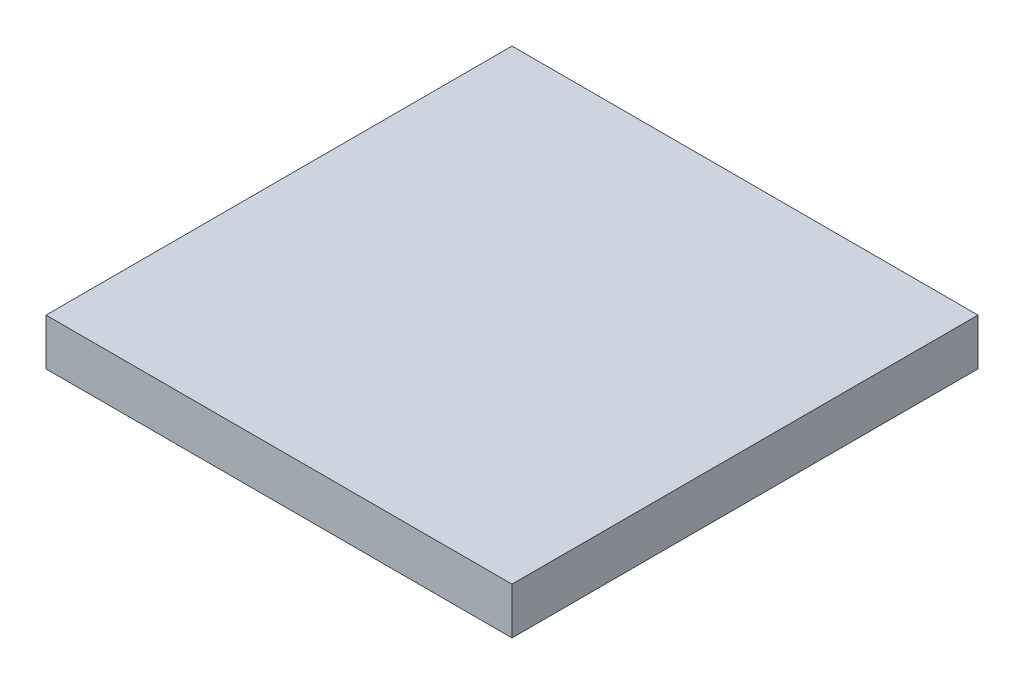
SolidWorks part; units mm, degrees
material "Glass"
ref_plane "Front Plane" through (0, 0, 0) normal (0, 0, 1) x (1, 0, 0)
ref_plane "Top Plane" through (0, 0, 0) normal (0, 1, 0) x (1, 0, 0)
ref_plane "Right Plane" through (0, 0, 0) normal (1, 0, 0) x (0, 0, -1)
sketch "Sketch1" plane through (0, 0, 0) normal (0, 1, 0) x (1, 0, 0)
  line L1 (-10, 10) -> (10, 10)
  line L2 (-10, 10) -> (-10, -10)
  line L3 (-10, -10) -> (10, -10)
  line L4 (10, 10) -> (10, -10)
  line L5 (-10, 10) -> (10, -10) construction
  line L6 (-10, -10) -> (10, 10) construction
  point P0 (0, 0)
  dimension "D1" = 20
  dimension "D2" = 20
extrude "Boss-Extrude1" add sketch "Sketch1" along normal blind 2
